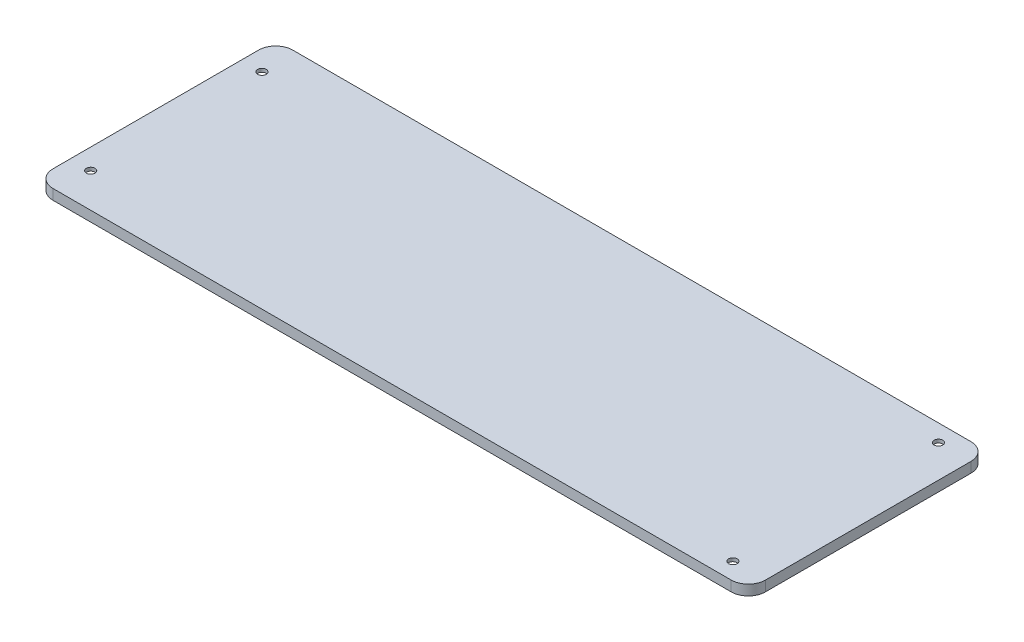
SolidWorks part; units mm, degrees
ref_plane "Front Plane" through (0, 0, 0) normal (0, 0, 1) x (1, 0, 0)
ref_plane "Top Plane" through (0, 0, 0) normal (0, 1, 0) x (1, 0, 0)
ref_plane "Right Plane" through (0, 0, 0) normal (1, 0, 0) x (0, 0, -1)
sketch "Sketch1" plane through (0, 0, 0) normal (0, 1, 0) x (1, 0, 0)
  line L1 (-104, 35) -> (104, 35)
  line L2 (-104, 35) -> (-104, -35)
  line L3 (-104, -35) -> (104, -35)
  line L4 (104, 35) -> (104, -35)
  line L5 (-104, 35) -> (104, -35) construction
  line L6 (-104, -35) -> (104, 35) construction
  circle A0 centre (-98, 25) radius 1.25
  circle A1 centre (-98, -25) radius 1.25
  circle A2 centre (94.5, 30) radius 1.25
  circle A3 centre (94.5, -30) radius 1.25
  point P0 (0, 0)
  dimension "D3" = 2.5
  dimension "D6" = 2.5
  dimension "D9" = 2.5
  dimension "D10" = 2.5
  dimension "D1" = 208
  dimension "D2" = 70
  dimension "D4" = 6
  dimension "D5" = 10
  dimension "D7" = 10
  dimension "D8" = 6
  dimension "D11" = 9.5
  dimension "D12" = 5
  dimension "D13" = 9.5
  dimension "D14" = 5
extrude "Boss-Extrude1" add sketch "Sketch1" along normal blind 3
fillet "Fillet1" radius 5 4 edges at (104, 1.5, 35) (104, 1.5, -35) (-104, 1.5, -35) (-104, 1.5, 35)
sketch "Sketch2" plane through (0, 0, 0) normal (0, 1, 0) x (1, 0, 0)
  circle A0 centre (-98, 25) radius 5
  circle A1 centre (94.5, 30) radius 4.75
  circle A2 centre (94.5, -30) radius 4.75
  circle A3 centre (-98, -25) radius 5
  dimension "D1" = 10
  dimension "D2" = 9.5
  dimension "D3" = 9.5
  dimension "D4" = 10
extrude "Cut-Extrude2" cut sketch "Sketch2" along normal blind 2
